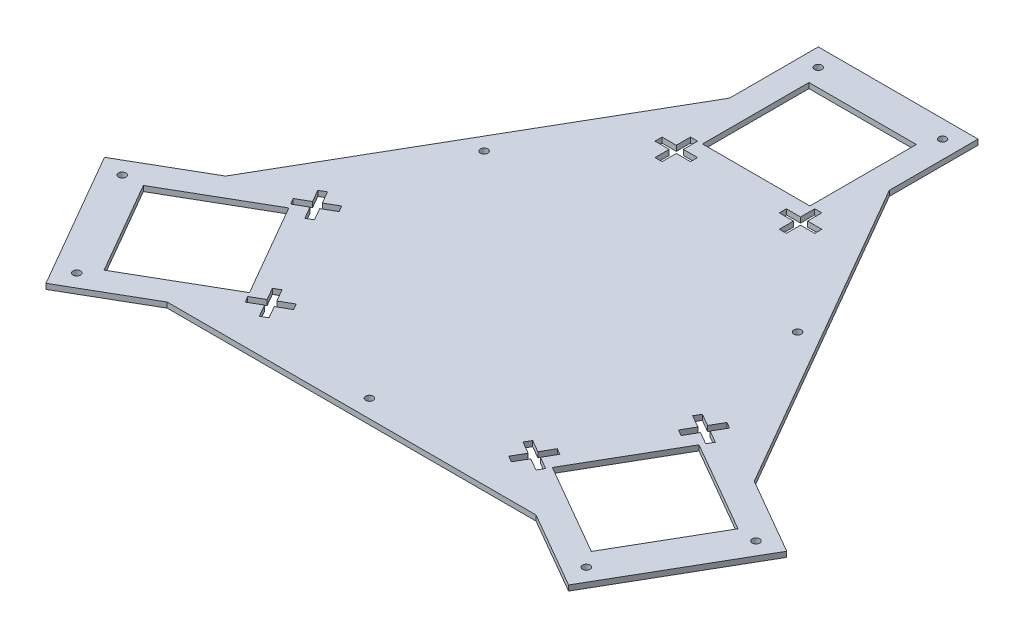
SolidWorks part; units mm, degrees
material "Alliage 2024"
ref_plane "Plan de face" through (0, 0, 0) normal (0, 0, 1) x (1, 0, 0)
ref_plane "Plan de dessus" through (0, 0, 0) normal (0, 1, 0) x (1, 0, 0)
ref_plane "Plan de droite" through (0, 0, 0) normal (1, 0, 0) x (0, 0, -1)
sketch "Esquisse1" plane through (0, 0, 0) normal (0, 1, 0) x (1, 0, 0)
  line L0 (0, 0) -> (0, 282.7427) construction
  line L1 (-53.6062, -30.9496) -> (0, 0) construction
  line L2 (0, 0) -> (52.3334, -30.2147) construction
  line L3 (-45, 195.9808) -> (-45, 145.9808)
  line L4 (-45, 195.9808) -> (45, 195.9808)
  line L6 (45, 195.9808) -> (45, 145.9808)
  line L7 (167.5288, -61.7931) -> (137.2788, -114.1876)
  line L8 (115.5673, -31.7931) -> (85.3173, -84.1876)
  line L9 (192.2243, -59.0192) -> (147.2243, -136.9615)
  line L10 (192.2243, -59.0192) -> (148.923, -34.0192)
  line L12 (147.2243, -136.9615) -> (103.923, -111.9615)
  line L13 (-147.2243, -136.9615) -> (-192.2243, -59.0192)
  line L14 (-147.2243, -136.9615) -> (-103.923, -111.9615)
  line L16 (-192.2243, -59.0192) -> (-148.923, -34.0192)
  line L17 (167.5288, -61.7931) -> (115.5673, -31.7931)
  line L18 (-30.25, 175.9808) -> (30.25, 175.9808)
  line L19 (-30.25, 175.9808) -> (-30.25, 115.9808)
  line L20 (-30.25, 115.9808) -> (30.25, 115.9808)
  line L21 (30.25, 175.9808) -> (30.25, 115.9808)
  line L22 (137.2788, -114.1876) -> (85.3173, -84.1876)
  line L23 (-137.2788, -114.1876) -> (-167.5288, -61.7931)
  line L24 (-85.3173, -84.1876) -> (-115.5673, -31.7931)
  line L25 (-137.2788, -114.1876) -> (-85.3173, -84.1876)
  line L26 (-167.5288, -61.7931) -> (-115.5673, -31.7931)
  line L27 (0, 0) -> (217.6804, -125.6779) construction
  line L28 (0, 0) -> (-268.6375, -155.0979) construction
  line L29 (-45, 145.9808) -> (45, 145.9808) construction
  line L30 (148.923, -34.0192) -> (103.923, -111.9615) construction
  line L31 (-103.923, -111.9615) -> (-148.923, -34.0192) construction
  line L32 (-45, 145.9808) -> (-148.923, -34.0192)
  line L33 (148.923, -34.0192) -> (45, 145.9808)
  line L34 (-103.923, -111.9615) -> (103.923, -111.9615)
  line L35 (0, 0) -> (-45, 25.9808) construction
  line L36 (0, 0) -> (45, 25.9808) construction
  line L37 (0, 0) -> (0, -51.9615) construction
  point P5 (0, 87.5)
  dimension "D1" = 60
  dimension "D2" = 60
  dimension "D3" = 170
  dimension "D4" = 90
  dimension "D6" = 60.5
  dimension "D7" = 60
  dimension "D8" = 170
  dimension "D9" = 20
  dimension "D10" = 14.75
  dimension "D11" = 3
  dimension "D12" = 120
  dimension "D13" = 120
  dimension "D15" = 50
  dimension "D16" = 3
  dimension "D5" = 3
  dimension "D14" = 3
extrude "Boss.-Extru.1" add sketch "Esquisse1" along normal blind 3 contours L14 L34 L12 L9 L10 L33 L6 L4 L3 L32 L16 L13 L23 L26 L24 L25 L7 L22 L8 L17 L18 L21 L20 L19
sketch "Esquisse2" plane through (0, 3, 0) normal (0, 1, 0) x (1, 0, 0)
  line L0 (-30.25, 145.9808) -> (30.25, 145.9808) construction
  line L1 (-30.25, 175.9808) -> (-30.25, 115.9808) construction
  line L2 (30.25, 175.9808) -> (30.25, 115.9808) construction
  line L3 (0, 115.9808) -> (0, 175.9808) construction
  line L4 (-30.25, 115.9808) -> (30.25, 115.9808) construction
  line L5 (-30.25, 175.9808) -> (30.25, 175.9808) construction
  line L6 (0, 175.9808) -> (0, 195.9808) construction
  line L7 (-45, 195.9808) -> (45, 195.9808) construction
  line L8 (45, 185.9808) -> (0, 185.9808) construction
  line L9 (45, 195.9808) -> (45, 145.9808) construction
  line L115 (0, 185.9808) -> (-45, 185.9808) construction
  line L116 (-45, 195.9808) -> (-45, 145.9808) construction
  line L118 (-35, 195.9808) -> (-35, 175.9808) construction
  line L120 (-45, 195.9808) -> (-25, 195.9808) construction
  line L121 (-45, 195.9808) -> (-45, 175.9808) construction
  line L122 (-45, 175.9808) -> (-25, 175.9808) construction
  line L123 (-25, 195.9808) -> (-25, 175.9808) construction
  line L124 (-45, 195.9808) -> (-25, 175.9808) construction
  line L125 (-45, 175.9808) -> (-25, 195.9808) construction
  line L126 (-96.9615, 55.9808) -> (169.7243, -97.9904) construction
  line L127 (-45, 145.9808) -> (-148.923, -34.0192) construction
  line L128 (192.2243, -59.0192) -> (147.2243, -136.9615) construction
  line L130 (0, -111.9615) -> (0, 115.9808) construction
  line L131 (-103.923, -111.9615) -> (103.923, -111.9615) construction
  line L133 (96.9615, 55.9808) -> (-169.7243, -97.9904) construction
  line L134 (148.923, -34.0192) -> (45, 145.9808) construction
  line L135 (-147.2243, -136.9615) -> (-192.2243, -59.0192) construction
  line L138 (74.641, 54.641) -> (91.9615, 64.641) construction
  line L139 (74.641, 54.641) -> (84.641, 37.3205) construction
  line L140 (84.641, 37.3205) -> (101.9615, 47.3205) construction
  line L141 (91.9615, 64.641) -> (101.9615, 47.3205) construction
  line L142 (74.641, 54.641) -> (101.9615, 47.3205) construction
  line L143 (84.641, 37.3205) -> (91.9615, 64.641) construction
  line L144 (148.923, -34.0192) -> (45, 145.9808) construction
  line L146 (-138.5641, -131.9615) -> (-161.0641, -92.9904) construction
  line L147 (-147.2243, -136.9615) -> (-103.923, -111.9615) construction
  line L149 (-152.2243, -128.3013) -> (-129.5565, -115.214) construction
  line L150 (-147.2243, -136.9615) -> (-123.5641, -123.3013) construction
  line L151 (10, -91.9615) -> (-10, -91.9615) construction
  line L152 (10, -91.9615) -> (10, -111.9615) construction
  line L153 (10, -91.9615) -> (-10, -111.9615) construction
  line L154 (-10, -91.9615) -> (10, -111.9615) construction
  line L155 (-10, -91.9615) -> (-10, -111.9615) construction
  line L156 (0, -111.9615) -> (0, 195.9808) construction
  line L157 (10, -111.9615) -> (-10, -111.9615) construction
  line L158 (-84.641, 37.3205) -> (-74.641, 54.641) construction
  line L159 (-84.641, 37.3205) -> (-101.9615, 47.3205) construction
  line L160 (-84.641, 37.3205) -> (-91.9615, 64.641) construction
  line L161 (-74.641, 54.641) -> (-101.9615, 47.3205) construction
  line L162 (-74.641, 54.641) -> (-91.9615, 64.641) construction
  line L163 (-96.9615, 55.9808) -> (169.7243, -97.9904) construction
  line L164 (-101.9615, 47.3205) -> (-91.9615, 64.641) construction
  circle A79 centre (-35, 185.9808) radius 2.1
  circle A80 centre (35, 185.9808) radius 2.1
  circle A81 centre (-143.5641, -123.3013) radius 2.1
  circle A82 centre (-178.5641, -62.6795) radius 2.1
  circle A83 centre (178.5641, -62.6795) radius 2.1
  circle A84 centre (143.5641, -123.3013) radius 2.1
  circle A85 centre (88.3013, 50.9808) radius 2.1
  circle A86 centre (0, -101.9615) radius 2.1
  circle A87 centre (-88.3013, 50.9808) radius 2.1
  point P16 (-34.75, 190.9808)
  point P19 (-34.75, 180.9808)
  point P20 (-28.75, 186.9808)
  point P23 (-38.75, 186.9808)
  point P45 (-32.75, 190.9808)
  point P46 (-32.75, 180.9808)
  point P47 (-28.75, 184.9808)
  point P48 (-38.75, 184.9808)
  point P715 (0, 0)
  point P738 (88.3013, 50.9808)
  dimension "D1" = 4.2
  dimension "D11" = 4.2
  dimension "D3" = 20
  dimension "D4" = 20
  dimension "D2" = 10
  dimension "D6" = 20
  dimension "D7" = 20
  dimension "D8" = 90
  dimension "D9" = 90
  dimension "D10" = 10
  dimension "D12" = 10
  dimension "D13" = 90
  dimension "D14" = 10
  dimension "D15" = 0
  dimension "D5" = 3
  dimension "D16" = 3
extrude "Enlèv. mat.-Extru.1" cut sketch "Esquisse2" against normal through all
sketch "Esquisse6" plane through (0, 3, 0) normal (0, 1, 0) x (1, 0, 0)
  line L0 (-35, 105.9808) -> (-35, 115.9808) construction
  line L1 (0, 175.9808) -> (0, 115.9808) construction
  line L2 (-30.25, 175.9808) -> (30.25, 175.9808) construction
  line L3 (-30.25, 115.9808) -> (30.25, 115.9808) construction
  line L4 (-35, 105.9808) -> (-35, 95.9808) construction
  line L5 (-45, 95.9808) -> (-25, 95.9808)
  line L6 (-45, 95.9808) -> (-45, 115.9808)
  line L7 (-45, 115.9808) -> (-25, 115.9808)
  line L8 (-25, 95.9808) -> (-25, 115.9808)
  line L9 (-45, 95.9808) -> (-25, 115.9808) construction
  line L10 (-45, 115.9808) -> (-25, 95.9808) construction
  line L11 (-45, 105.9808) -> (-25, 105.9808) construction
  line L24 (-35, 115.9808) -> (-35, 185.9808) construction
  line L25 (-33, 105.9808) -> (-33, 95.9808)
  line L26 (-33, 105.9808) -> (-33, 115.9808)
  line L27 (-45, 103.9808) -> (-25, 103.9808)
  line L28 (-37, 105.9808) -> (-37, 95.9808)
  line L29 (-37, 105.9808) -> (-37, 115.9808)
  line L30 (-45, 107.9808) -> (-25, 107.9808)
  line L31 (45, 105.9808) -> (25, 105.9808) construction
  line L32 (45, 115.9808) -> (25, 95.9808) construction
  line L33 (45, 95.9808) -> (25, 115.9808) construction
  line L34 (35, 105.9808) -> (35, 95.9808) construction
  line L35 (35, 105.9808) -> (35, 115.9808) construction
  line L36 (45, 107.9808) -> (25, 107.9808)
  line L37 (37, 105.9808) -> (37, 115.9808)
  line L38 (37, 105.9808) -> (37, 95.9808)
  line L39 (45, 103.9808) -> (25, 103.9808)
  line L40 (33, 105.9808) -> (33, 115.9808)
  line L41 (33, 105.9808) -> (33, 95.9808)
  line L42 (25, 95.9808) -> (25, 115.9808)
  line L43 (45, 115.9808) -> (25, 115.9808)
  line L44 (45, 95.9808) -> (45, 115.9808)
  line L45 (45, 95.9808) -> (25, 95.9808)
  line L46 (96.9615, 55.9808) -> (-169.7243, -97.9904) construction
  line L47 (148.923, -34.0192) -> (45, 145.9808) construction
  line L48 (-147.2243, -136.9615) -> (-192.2243, -59.0192) construction
  line L49 (-96.9615, 55.9808) -> (169.7243, -97.9904) construction
  line L50 (-45, 145.9808) -> (-148.923, -34.0192) construction
  line L51 (192.2243, -59.0192) -> (147.2243, -136.9615) construction
  line L52 (0, -111.9615) -> (0, 195.9808) construction
  line L53 (-103.923, -111.9615) -> (103.923, -111.9615) construction
  line L54 (-45, 195.9808) -> (45, 195.9808) construction
  line L55 (109.282, -22.6795) -> (117.9423, -27.6795) construction
  line L56 (109.282, -22.6795) -> (100.6218, -17.6795) construction
  line L57 (105.6218, -9.0192) -> (112.9423, -36.3397) construction
  line L58 (122.9423, -19.0192) -> (95.6218, -26.3397) construction
  line L59 (114.282, -14.0192) -> (104.282, -31.3397) construction
  line L60 (105.6218, -9.0192) -> (95.6218, -26.3397)
  line L61 (105.6218, -9.0192) -> (122.9423, -19.0192)
  line L62 (122.9423, -19.0192) -> (112.9423, -36.3397)
  line L63 (95.6218, -26.3397) -> (112.9423, -36.3397)
  line L64 (108.282, -24.4115) -> (99.6218, -19.4115)
  line L65 (108.282, -24.4115) -> (116.9423, -29.4115)
  line L66 (112.55, -13.0192) -> (102.55, -30.3397)
  line L67 (110.282, -20.9474) -> (101.6218, -15.9474)
  line L68 (110.282, -20.9474) -> (118.9423, -25.9474)
  line L69 (116.0141, -15.0192) -> (106.0141, -32.3397)
  line L70 (69.282, -91.9615) -> (79.282, -74.641) construction
  line L71 (77.9423, -96.9615) -> (70.6218, -69.641) construction
  line L72 (60.6218, -86.9615) -> (87.9423, -79.641) construction
  line L73 (74.282, -83.3013) -> (65.6218, -78.3013) construction
  line L74 (74.282, -83.3013) -> (82.9423, -88.3013) construction
  line L75 (71.0141, -92.9615) -> (81.0141, -75.641)
  line L76 (73.282, -85.0333) -> (81.9423, -90.0333)
  line L77 (73.282, -85.0333) -> (64.6218, -80.0333)
  line L78 (67.55, -90.9615) -> (77.55, -73.641)
  line L79 (75.282, -81.5692) -> (83.9423, -86.5692)
  line L80 (75.282, -81.5692) -> (66.6218, -76.5692)
  line L81 (70.6218, -69.641) -> (87.9423, -79.641)
  line L82 (77.9423, -96.9615) -> (87.9423, -79.641)
  line L83 (60.6218, -86.9615) -> (77.9423, -96.9615)
  line L84 (60.6218, -86.9615) -> (70.6218, -69.641)
  line L85 (-74.282, -83.3013) -> (-82.9423, -88.3013) construction
  line L86 (-74.282, -83.3013) -> (-65.6218, -78.3013) construction
  line L87 (-60.6218, -86.9615) -> (-87.9423, -79.641) construction
  line L88 (-77.9423, -96.9615) -> (-70.6218, -69.641) construction
  line L89 (-69.282, -91.9615) -> (-79.282, -74.641) construction
  line L90 (-60.6218, -86.9615) -> (-70.6218, -69.641)
  line L91 (-60.6218, -86.9615) -> (-77.9423, -96.9615)
  line L92 (-77.9423, -96.9615) -> (-87.9423, -79.641)
  line L93 (-70.6218, -69.641) -> (-87.9423, -79.641)
  line L94 (-75.282, -81.5692) -> (-66.6218, -76.5692)
  line L95 (-75.282, -81.5692) -> (-83.9423, -86.5692)
  line L96 (-67.55, -90.9615) -> (-77.55, -73.641)
  line L97 (-73.282, -85.0333) -> (-64.6218, -80.0333)
  line L98 (-73.282, -85.0333) -> (-81.9423, -90.0333)
  line L99 (-71.0141, -92.9615) -> (-81.0141, -75.641)
  line L100 (-114.282, -14.0192) -> (-104.282, -31.3397) construction
  line L101 (-122.9423, -19.0192) -> (-95.6218, -26.3397) construction
  line L102 (-105.6218, -9.0192) -> (-112.9423, -36.3397) construction
  line L103 (-109.282, -22.6795) -> (-100.6218, -17.6795) construction
  line L104 (-109.282, -22.6795) -> (-117.9423, -27.6795) construction
  line L105 (-116.0141, -15.0192) -> (-106.0141, -32.3397)
  line L106 (-110.282, -20.9474) -> (-118.9423, -25.9474)
  line L107 (-110.282, -20.9474) -> (-101.6218, -15.9474)
  line L108 (-112.55, -13.0192) -> (-102.55, -30.3397)
  line L109 (-108.282, -24.4115) -> (-116.9423, -29.4115)
  line L110 (-108.282, -24.4115) -> (-99.6218, -19.4115)
  line L111 (-95.6218, -26.3397) -> (-112.9423, -36.3397)
  line L112 (-122.9423, -19.0192) -> (-112.9423, -36.3397)
  line L113 (-105.6218, -9.0192) -> (-122.9423, -19.0192)
  line L114 (-105.6218, -9.0192) -> (-95.6218, -26.3397)
  dimension "D1" = 2
  dimension "D2" = 20
  dimension "D3" = 20
  dimension "D4" = 2
extrude "Enlèv. mat.-Extru.2" cut sketch "Esquisse6" against normal through all contours L29 L30 L26 L7 | L30 L29 L28 L27 L25 L26 | L30 L6 L27 L28 L29 | L30 L26 L25 L27 L8 | L27 L28 L5 L25 | L42 L39 L41 L40 L36 | L37 L43 L40 L36 | L40 L41 L39 L38 L37 L36 | L39 L44 L36 L37 L38 | L45 L38 L39 L41 | L69 L61 L66 L67 L68 | L69 L68 L67 L66 L64 L65 | L66 L67 L60 L64 | L69 L65 L64 L66 L63 | L68 L69 L65 L62 | L84 L77 L78 L80 | L81 L78 L80 L79 L75 | L79 L80 L78 L77 L76 L75 | L76 L82 L79 L75 | L78 L83 L75 L76 L77 | L99 L95 L94 L96 L93 | L98 L99 L95 L92 | L99 L91 L96 L97 L98 | L96 L97 L90 L94 | L106 L112 L109 L105 | L108 L113 L105 L106 L107 | L109 L110 L108 L107 L106 L105 | L114 L107 L108 L110 | L111 L108 L110 L109 L105 | L99 L98 L97 L96 L94 L95
equation "\"D2@Esquisse2\"=\"D4@Esquisse2\"/2"
equation "\"D6@Esquisse2\"=\"D3@Esquisse2\""
equation "\"D7@Esquisse2\"=\"D3@Esquisse2\""
equation "\"D10@Esquisse2\"=\"D2@Esquisse2\""
equation "\"D11@Esquisse2\"=\"D1@Esquisse2\""
